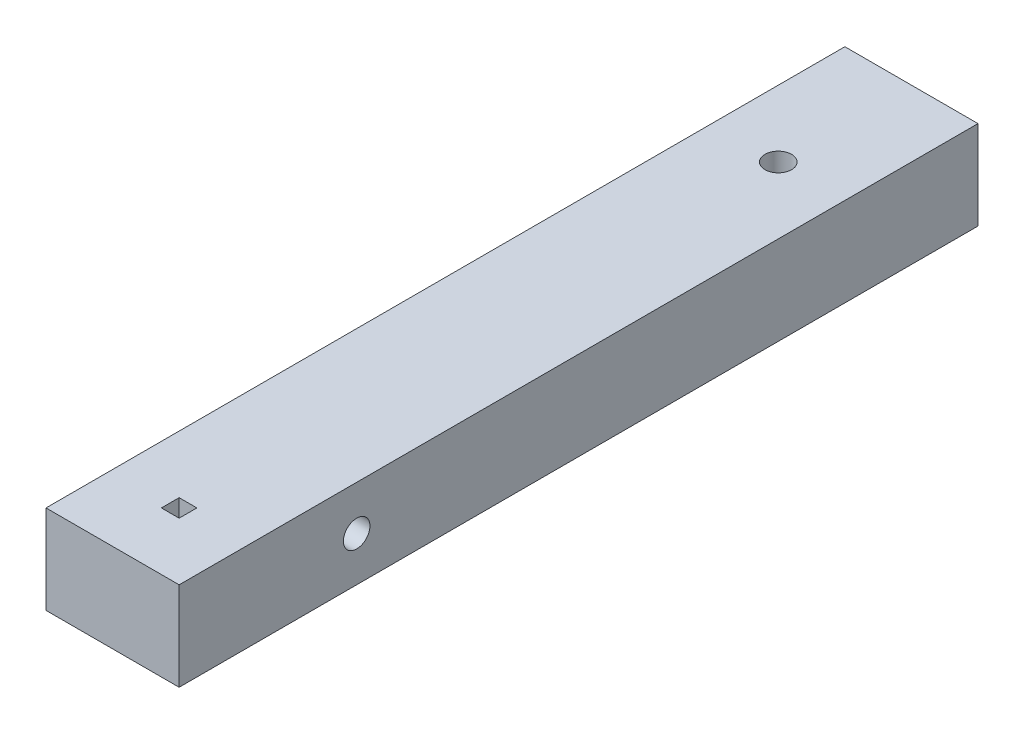
SolidWorks part; units mm, degrees
ref_plane "Plan de face" through (0, 0, 0) normal (0, 0, 1) x (1, 0, 0)
ref_plane "Plan de dessus" through (0, 0, 0) normal (0, 1, 0) x (1, 0, 0)
ref_plane "Plan de droite" through (0, 0, 0) normal (1, 0, 0) x (0, 0, -1)
sketch "Sketch1" plane through (0, 0, 0) normal (0, 1, 0) x (1, 0, 0)
  line L1 (7.5, -45) -> (-7.5, -45)
  line L2 (7.5, -45) -> (7.5, 45)
  line L3 (7.5, 45) -> (-7.5, 45)
  line L4 (-7.5, -45) -> (-7.5, 45)
  line L5 (7.5, -45) -> (-7.5, 45) construction
  line L6 (7.5, 45) -> (-7.5, -45) construction
  point P0 (0, 0)
  dimension "D1" = 90
  dimension "D2" = 15
extrude "Boss-Extrude1" add sketch "Sketch1" along normal blind 10
sketch "Sketch2" plane through (7.5, 0, 0) normal (1, 0, 0) x (0, 0, -1)
  line L0 (-45, 10) -> (-45, 0) construction
  line L1 (-45, 0) -> (45, 0) construction
  circle A0 centre (-25, 5) radius 1.5
  point P2 (-45, 5)
  dimension "D1" = 20
  dimension "D2" = 5
extrude "Cut-Extrude1" cut sketch "Sketch2" against normal through all
sketch "Sketch5" plane through (0, 0, 0) normal (0, -1, 0) x (1, 0, 0)
  line L0 (-7.5, -45) -> (-7.5, 45) construction
  line L1 (1, 36.5) -> (-1, 36.5)
  line L2 (1, 36.5) -> (1, 38.5)
  line L3 (1, 38.5) -> (-1, 38.5)
  line L4 (-1, 36.5) -> (-1, 38.5)
  line L5 (1, 36.5) -> (-1, 38.5) construction
  line L6 (1, 38.5) -> (-1, 36.5) construction
  line L7 (-7.5, 45) -> (7.5, 45) construction
  point P0 (0, 37.5)
  dimension "D1" = 2
  dimension "D2" = 2
  dimension "D3" = 7.5
  dimension "D4" = 7.5
extrude "Cut-Extrude4" cut sketch "Sketch5" against normal through all
sketch "Sketch6" plane through (0, 10, 0) normal (0, 1, 0) x (-1, 0, 0)
  line L0 (-7.5, -45) -> (7.5, -45) construction
  circle A0 centre (0, -30) radius 1.5
  point P2 (0, -45)
  dimension "D1" = 15
  dimension "D2" = 3
extrude "Cut-Extrude5" cut sketch "Sketch6" against normal through all
sketch "Sketch7" plane through (0, 0, -45) normal (0, 0, -1) x (-1, 0, 0)
  line L1 (1, 4) -> (-1, 4)
  line L2 (1, 4) -> (1, 6)
  line L3 (1, 6) -> (-1, 6)
  line L4 (-1, 4) -> (-1, 6)
  line L5 (1, 4) -> (-1, 6) construction
  line L6 (1, 6) -> (-1, 4) construction
  line L7 (-7.5, 10) -> (-7.5, 0) construction
  point P0 (0, 5)
  dimension "D1" = 2
  dimension "D2" = 2
  dimension "D3" = 7.5
  dimension "D4" = 5
extrude "Cut-Extrude6" cut sketch "Sketch7" against normal blind 15
